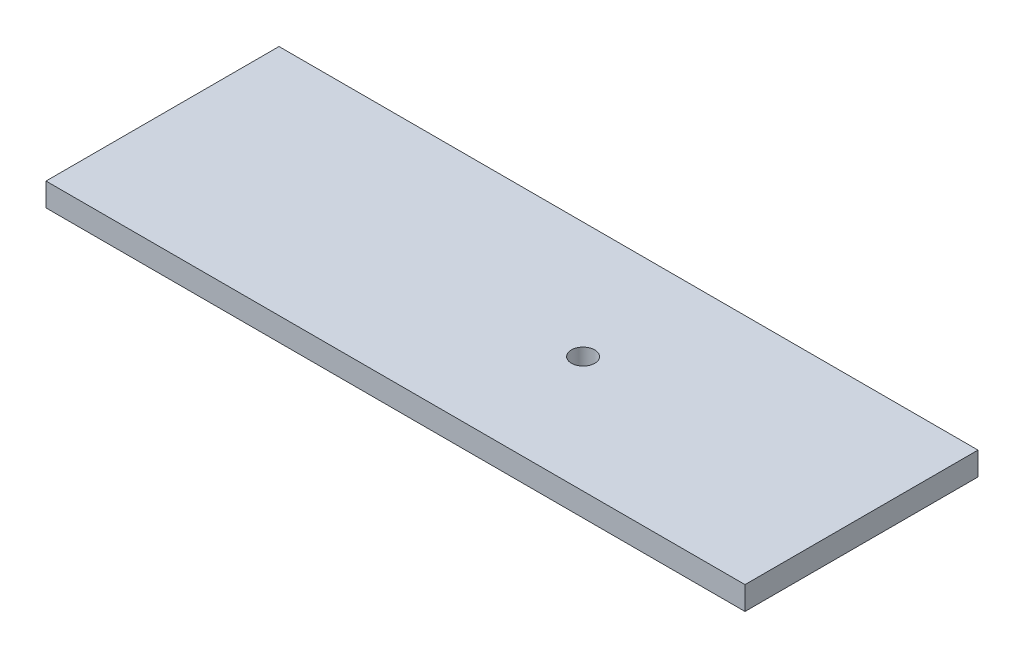
SolidWorks part; units mm, degrees
ref_plane "Alzado" through (0, 0, 0) normal (0, 0, 1) x (1, 0, 0)
ref_plane "Planta" through (0, 0, 0) normal (0, 1, 0) x (1, 0, 0)
ref_plane "Vista lateral" through (0, 0, 0) normal (1, 0, 0) x (0, 0, -1)
sketch "Croquis1" plane through (0, 0, 0) normal (0, 1, 0) x (1, 0, 0)
  line L1 (0, 0) -> (300, 0)
  line L2 (0, 0) -> (0, 100)
  line L3 (0, 100) -> (300, 100)
  line L4 (300, 0) -> (300, 100)
  dimension "D1" = 100
  dimension "D2" = 300
extrude "Saliente-Extruir1" add sketch "Croquis1" along normal blind 10
sketch "Croquis2" plane through (0, 10, 0) normal (0, 1, 0) x (1, 0, 0)
  line L0 (0, 100) -> (0, 0) construction
  line L1 (300, 0) -> (300, 100) construction
  circle A0 centre (180.5, 50) radius 5
  point P7 (300, 50)
  dimension "D1" = 180.5
  dimension "D2" = 10
extrude "Cortar-Extruir1" cut sketch "Croquis2" against normal blind 10
